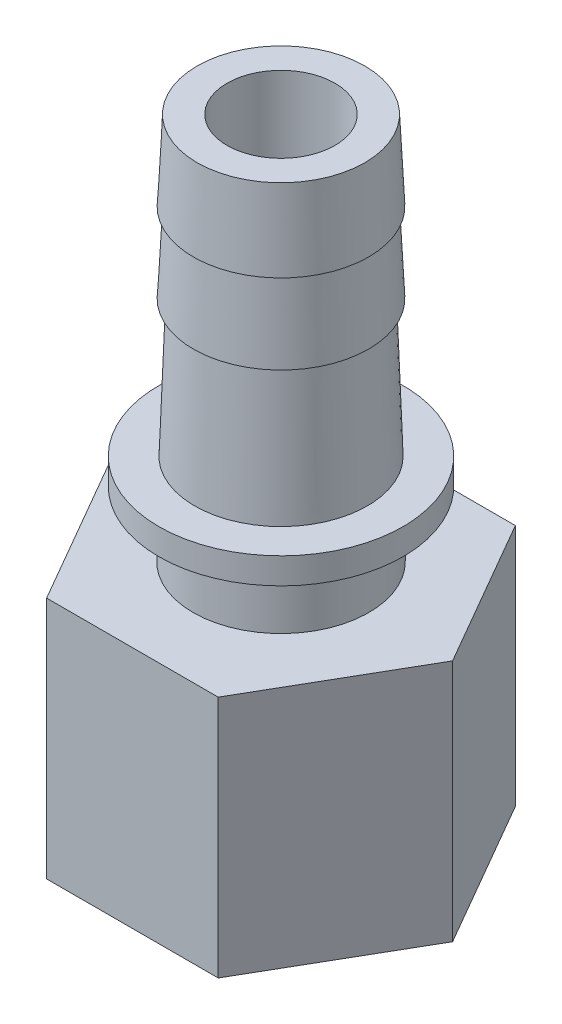
SolidWorks part; units mm, degrees
ref_plane "Front Plane" through (0, 0, 0) normal (0, 0, 1) x (1, 0, 0)
ref_plane "Top Plane" through (0, 0, 0) normal (0, 1, 0) x (1, 0, 0)
ref_plane "Right Plane" through (0, 0, 0) normal (1, 0, 0) x (0, 0, -1)
sketch "Sketch1" plane through (0, 0, 0) normal (0, 1, 0) x (1, 0, 0)
  line L1 (10.0783, 17.4562) -> (-10.0783, 17.4562)
  line L2 (-10.0783, 17.4562) -> (-20.1566, 0)
  line L3 (-20.1566, 0) -> (-10.0783, -17.4562)
  line L4 (-10.0783, -17.4562) -> (10.0783, -17.4562)
  line L5 (10.0783, -17.4562) -> (20.1566, 0)
  line L6 (20.1566, 0) -> (10.0783, 17.4562)
  circle A0 centre (0, 0) radius 17.4562 construction
  dimension "D1" = 34.9123
extrude "Boss-Extrude1" add sketch "Sketch1" along normal blind 28.575
sketch "Sketch2" plane through (0, 28.575, 0) normal (0, 1, 0) x (1, 0, 0)
  circle A0 centre (0, 0) radius 10.3251
  dimension "D1" = 20.6502
extrude "Boss-Extrude2" add sketch "Sketch2" along normal blind 7.6962
sketch "Sketch3" plane through (0, 36.2712, 0) normal (0, 1, 0) x (1, 0, 0)
  circle A0 centre (0, 0) radius 14.351
  dimension "D1" = 28.702
extrude "Boss-Extrude3" add sketch "Sketch3" along normal blind 3.0607
sketch "Sketch4" plane through (0, 0, 0) normal (0, 0, 1) x (1, 0, 0)
  line L0 (0, 39.3319) -> (10.1473, 39.3319)
  line L1 (0, -19.2018) -> (0, 19.2018) construction
  line L2 (14.351, 39.3319) -> (-14.351, 39.3319) construction
  line L3 (0, 39.3319) -> (-10.1473, 39.3319)
  line L4 (0, 55.3593) -> (9.6012, 55.3593)
  line L5 (0, 55.3593) -> (-9.6012, 55.3593)
  line L8 (-9.6012, 55.3593) -> (-10.1473, 39.3319)
  line L9 (9.6012, 55.3593) -> (10.1473, 39.3319)
  line L10 (0, 55.3593) -> (0, 39.3319)
  dimension "D1" = 10.1473
  dimension "D2" = 10.1473
  dimension "D3" = 9.6012
  dimension "D4" = 9.6012
  dimension "D5" = 16.0274
revolve "Revolve2" add sketch "Sketch4" angle 360 about L10
sketch "Sketch5" plane through (0, 0, 0) normal (0, 0, 1) x (1, 0, 0)
  line L0 (0, 55.3593) -> (10.2933, 55.3593)
  line L1 (0, 55.3593) -> (9.6012, 55.3593) construction
  line L2 (0, 55.3593) -> (0, 64.7319)
  line L3 (0, 64.7319) -> (9.8488, 64.7319)
  line L4 (10.2933, 55.3593) -> (9.8488, 64.7319)
  line L5 (0, 64.7319) -> (10.2934, 64.7319)
  line L6 (0, 64.7319) -> (0, 74.1045)
  line L7 (0, 74.1045) -> (9.8488, 74.1045)
  line L8 (9.8488, 74.1045) -> (10.2934, 64.7319)
  line L9 (0, 74.1045) -> (9.8488, 74.1045)
  line L10 (10.2933, 74.1045) -> (9.8488, 83.4771)
  line L11 (9.8488, 92.8497) -> (10.2933, 83.4771)
  line L12 (0, 83.4771) -> (0, 92.8497)
  line L13 (0, 74.1045) -> (10.2933, 74.1045)
  line L14 (0, 74.1045) -> (0, 83.4771)
  line L15 (0, 83.4771) -> (9.8488, 83.4771)
  line L16 (0, 92.8497) -> (9.8488, 92.8497)
  line L17 (0, 83.4771) -> (10.2933, 83.4771)
  dimension "D1" = 10.2934
  dimension "D2" = 9.3726
  dimension "D3" = 9.8488
  dimension "D4" = 10.2934
  dimension "D5" = 9.3726
  dimension "D6" = 87.285
  dimension "D7" = 9.3726
  dimension "D8" = 9.8488
  dimension "D9" = 9.8489
  dimension "D10" = 9.3726
  dimension "D11" = 87.285
  dimension "D12" = 87.285
revolve "Revolve3" add sketch "Sketch5" angle 360 about L2
sketch "Sketch6" plane through (0, 0, 0) normal (0, -1, 0) x (-1, 0, 0)
  circle A0 centre (0, 0) radius 11.7348
  dimension "D1" = 23.4696
extrude "Cut-Extrude1" cut sketch "Sketch6" against normal blind 19.9771
sketch "Sketch7" plane through (0, 92.8497, 0) normal (0, 1, 0) x (1, 0, 0)
  circle A0 centre (0, 0) radius 6.3373
  dimension "D1" = 12.6746
extrude "Cut-Extrude2" cut sketch "Sketch7" against normal blind 72.2884
sketch "Sketch14" plane through (0, 0, 0) normal (0, 0, 1) x (1, 0, 0)
  line L0 (11.7348, 19.9771) -> (6.3373, 20.5613)
  line L1 (-11.7348, 19.9771) -> (11.7348, 19.9771) construction
  line L2 (6.3373, 20.5613) -> (-6.3373, 20.5613) construction
  line L4 (6.3373, 20.5613) -> (0, 20.5613)
  line L5 (11.7348, 19.9771) -> (0, 19.9771)
  line L6 (0, 20.5613) -> (0, 19.9771)
  line L7 (0, 20.5613) -> (6.3373, 20.5613)
  dimension "D1" = 6.3373
  dimension "D2" = 5.429
revolve "Cut-Revolve1" cut sketch "Sketch14" angle 360 about L6
thread "Thread1" pitch 2.1167 start angle 0, offset 0, length 0, pitch 2.1167, diameter 23.4696
ref_plane "Plane1" through (11.7348, 0, 0) normal (0, 0, 1) x (1, 0, 0)
sketch "Thread Profile1" plane through (11.7348, 0, 0) normal (0, 0, 1) x (1, 0, 0)
  line L0 (0, 0) -> (0, 2.1167) construction
  line L1 (0, 0) -> (1.1457, 0.6615)
  line L2 (1.1457, 0.6615) -> (1.1457, 0.926)
  line L3 (1.1457, 0.926) -> (0, 1.5875)
  line L4 (1.1457, 0.7937) -> (0, 0.7937) construction
  line L11 (0, 0) -> (0, 1.5875)
  point P2 (0, 0)
  dimension "Pitch" = 2.1167
  dimension "Profile_Angle" = 60
  dimension "Profile_Land" = 0.2646
  dimension "Profile_Height" = 1.1457
sketch "Sketch15" plane through (15.1175, 0, -8.7281) normal (0.866, 0, -0.5) x (-0.5, 0, -0.866)
  line L0 (-10.2934, 83.4771) -> (10.2933, 83.4771) construction
  line L1 (-10.2933, 74.1045) -> (10.2933, 74.1045) construction
  line L2 (-10.2934, 83.4771) -> (10.2933, 83.4771)
  line L3 (-10.2933, 74.1045) -> (10.2933, 74.1045)
  line L4 (10.2933, 74.1045) -> (10.2933, 99.5045)
  line L5 (-10.2933, 74.1045) -> (-10.2934, 99.5045)
  line L6 (-10.2934, 99.5045) -> (10.2933, 99.5045)
  dimension "D1" = 25.4
extrude "Cut-Extrude3" cut sketch "Sketch15" against normal through all both and the other way through all contours L5 L3 L4 L2 | L6 L5 L2 L4
